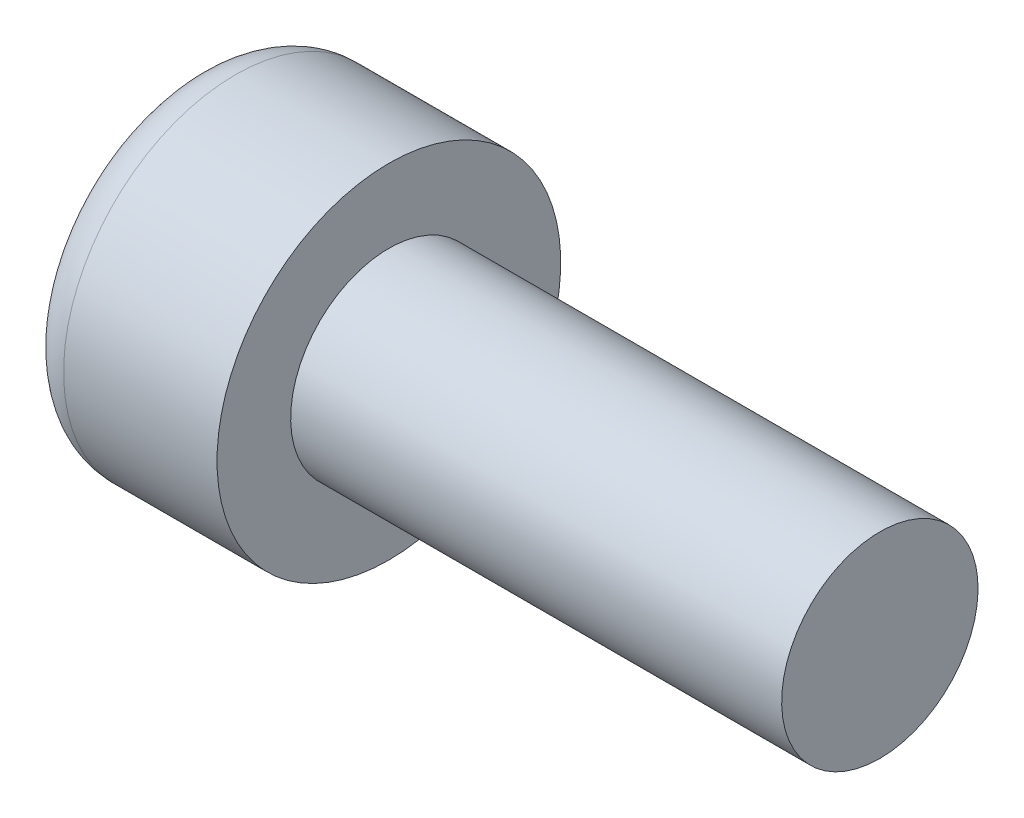
SolidWorks part; units mm, degrees
material "Plain Carbon Steel"
ref_plane "Front Plane" through (0, 0, 0) normal (0, 0, 1) x (1, 0, 0)
ref_plane "Top Plane" through (0, 0, 0) normal (0, 1, 0) x (1, 0, 0)
ref_plane "Right Plane" through (0, 0, 0) normal (1, 0, 0) x (0, 0, -1)
sketch "Sketch1" plane through (0, 0, 0) normal (0, 0, 1) x (1, 0, 0)
  line L0 (0, 0) -> (0, 2.625)
  line L1 (0.875, 3.5) -> (4, 3.5)
  line L2 (4, 3.5) -> (4, 2)
  line L3 (4, 2) -> (14, 2)
  line L4 (14, 2) -> (14, 0)
  line L5 (14, 0) -> (0, 0) construction
  line L6 (0.875, 2.625) -> (0.875, 1.75) construction
  line L7 (0.875, 1.75) -> (0.875, 0.875) construction
  line L8 (0.875, 0.875) -> (0.875, 0) construction
  line L9 (0.875, 3.5) -> (0.875, 2.625) construction
  line L10 (0, 0) -> (14, 0)
  arc A0 (0, 2.625) -> (0.875, 3.5) centre (0.875, 2.625) cw
  dimension "D1" = 4
  dimension "D2" = 7
  dimension "D3" = 4
  dimension "D4" = 10
revolve "Revolve1" add sketch "Sketch1" angle 360 about L10
sketch "Sketch2" plane through (0, 0, 0) normal (-1, 0, 0) x (0, 0, 1)
  line L1 (0, 1.7321) -> (-1.5, 0.866)
  line L2 (-1.5, 0.866) -> (-1.5, -0.866)
  line L3 (-1.5, -0.866) -> (0, -1.7321)
  line L4 (0, -1.7321) -> (1.5, -0.866)
  line L5 (1.5, -0.866) -> (1.5, 0.866)
  line L6 (1.5, 0.866) -> (0, 1.7321)
  circle A0 centre (0, 0) radius 1.5 construction
  dimension "D1" = 3
extrude "Cut-Extrude1" cut sketch "Sketch2" against normal blind 2
